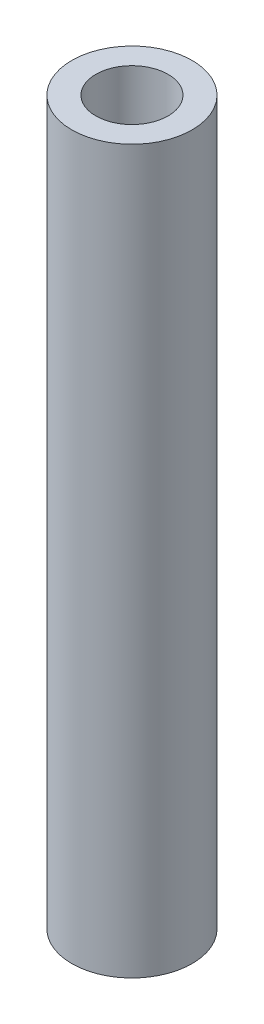
SolidWorks part; units mm, degrees
ref_plane "Front Plane" through (0, 0, 0) normal (0, 0, 1) x (1, 0, 0)
ref_plane "Top Plane" through (0, 0, 0) normal (0, 1, 0) x (1, 0, 0)
ref_plane "Right Plane" through (0, 0, 0) normal (1, 0, 0) x (0, 0, -1)
sketch "Sketch1" plane through (0, 0, 0) normal (0, 1, 0) x (1, 0, 0)
  circle A0 centre (0, 0) radius 2.5
  circle A1 centre (0, 0) radius 1.5
  dimension "D1" = 5
  dimension "D2" = 3
extrude "Boss-Extrude1" add sketch "Sketch1" along normal mid plane 30
ref_point "Point1"
